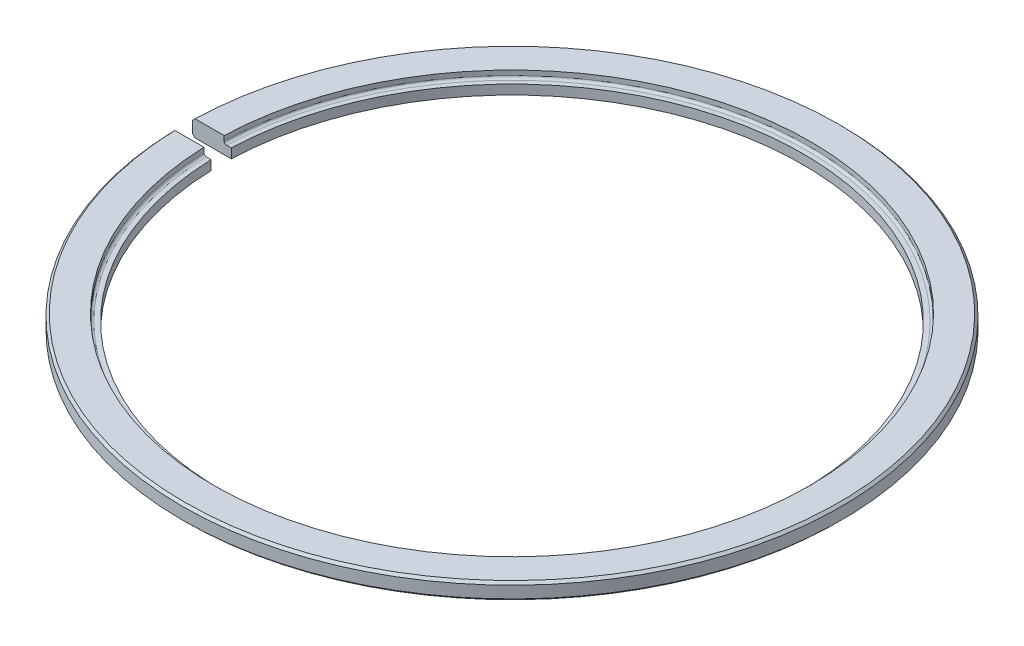
SolidWorks part; units mm, degrees
material "AISI 1045 Steel, cold drawn"
ref_plane "Front Plane" through (0, 0, 0) normal (0, 0, 1) x (1, 0, 0)
ref_plane "Top Plane" through (0, 0, 0) normal (0, 1, 0) x (1, 0, 0)
ref_plane "Right Plane" through (0, 0, 0) normal (1, 0, 0) x (0, 0, -1)
sketch "Sketch1" plane through (0, 0, 0) normal (0, 0, 1) x (1, 0, 0)
  line L0 (0, 0) -> (0, 6.5775) construction
  line L16 (35.2425, 0) -> (35.2425, 1.778)
  line L18 (35.2425, 1.778) -> (31.877, 1.778)
  line L19 (31.877, 1.778) -> (31.877, 1.016)
  line L20 (31.877, 1.016) -> (31.115, 1.016)
  line L21 (31.115, 1.016) -> (31.115, 0)
  line L22 (31.115, 0) -> (35.2425, 0)
  dimension "D1" = 1.016
  dimension "D2" = 0.762
  dimension "D3" = 1.778
  dimension "D4" = 62.23
  dimension "D5" = 70.485
revolve "Revolve1" add sketch "Sketch1" angle 360 about L0
fillet "Fillet1" radius 0.254 1 edges at (0, 1.016, -31.877)
chamfer "Chamfer1" distance 0.254 angle 45 2 edges at (0, 0, -35.2425) (0, 1.778, -35.2425)
sketch "Sketch2" plane through (0, 1.778, 0) normal (0, 1, 0) x (1, 0, 0)
  line L1 (-35.2425, -1.0795) -> (-31.0963, -1.0795)
  line L2 (-35.2425, -1.0795) -> (-35.2425, 1.0795)
  line L3 (-35.2425, 1.0795) -> (-31.0963, 1.0795)
  line L4 (-31.0963, -1.0795) -> (-31.0963, 1.0795)
  line L5 (-33.1694, 1.0795) -> (-33.1694, -1.0795) construction
  line L6 (-35.2425, 0) -> (-31.0963, 0) construction
  circle A5 centre (0, 0) radius 31.115 construction
  circle A6 centre (0, 0) radius 35.2425 construction
  point P0 (-33.1694, 0)
  dimension "D1" = 2.159
extrude "Cut-Extrude1" cut sketch "Sketch2" against normal through all
